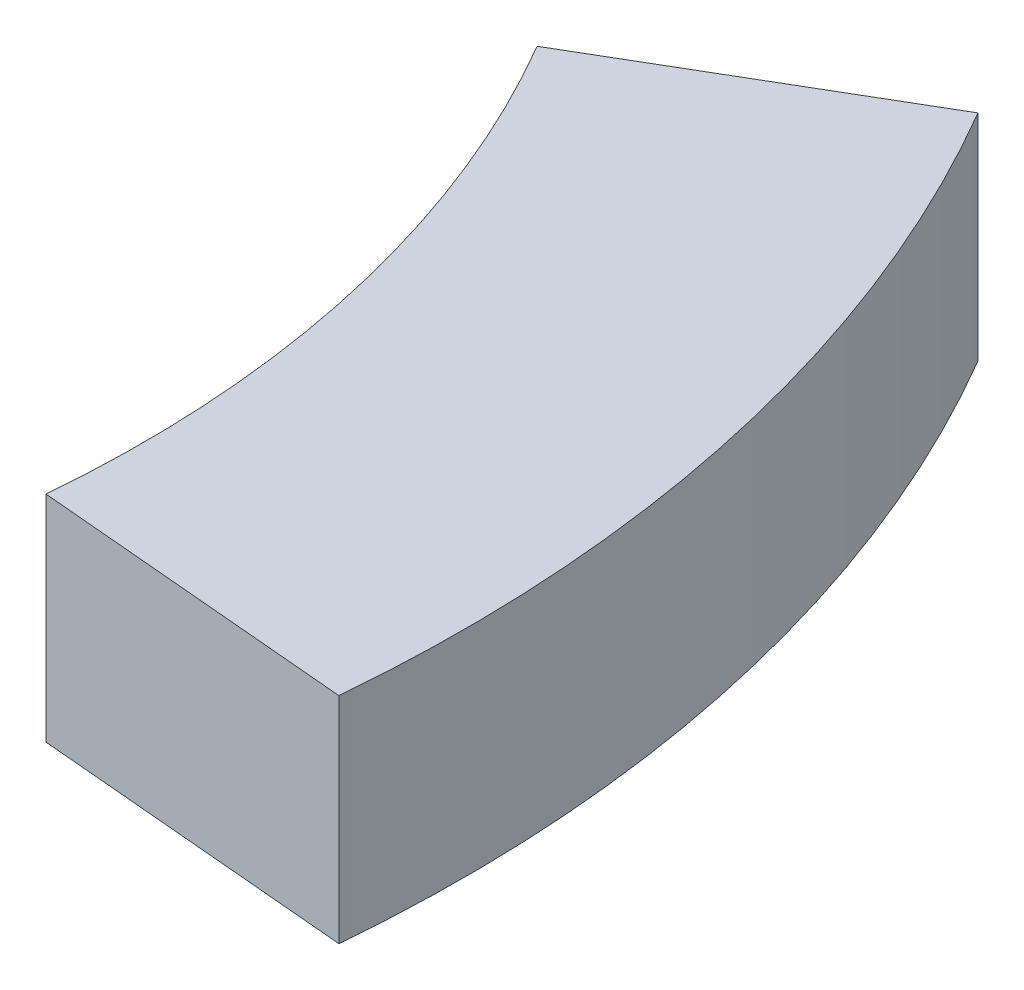
SolidWorks part; units mm, degrees
ref_plane "Front Plane" through (0, 0, 0) normal (0, 0, 1) x (1, 0, 0)
ref_plane "Top Plane" through (0, 0, 0) normal (0, 1, 0) x (1, 0, 0)
ref_plane "Right Plane" through (0, 0, 0) normal (1, 0, 0) x (0, 0, -1)
sketch "Sketch1" plane through (0, 0, 0) normal (0, 1, 0) x (1, 0, 0)
  line L0 (0, 0) -> (57.28, 0) construction
  line L1 (42.9687, 25.1345) -> (55.9162, 32.7082)
  line L2 (49.59, -4.3453) -> (64.5327, -5.6547)
  circle A0 centre (0, 0) radius 57.28 construction
  arc A1 (57.0614, -5) -> (49.4424, 28.9213) centre (0, 0) ccw construction
  arc A2 (64.5327, -5.6547) -> (55.9162, 32.7082) centre (0, 0) ccw
  arc A3 (49.59, -4.3453) -> (42.9687, 25.1345) centre (0, 0) ccw
  arc A4 (49.59, -4.3453) -> (64.5327, -5.6547) centre (57.0614, -5) ccw
  arc A5 (55.9162, 32.7082) -> (42.9687, 25.1345) centre (49.4424, 28.9213) ccw
  point P3 (51.7762, 24.4994)
  point P5 (55.8876, 12.5527)
  point P7 (57.28, 0)
  dimension "D1" = 114.56
  dimension "D5" = 7.5
  dimension "D2" = 25.11
  dimension "D3" = 5
  dimension "D4" = 5
extrude "Boss-Extrude1" add sketch "Sketch1" along normal blind 10 contours A3 L2 A2 L1
sketch "Sketch2" plane through (0, 0, 0) normal (0, -1, 0) x (-1, 0, 0)
  point P0 (-57.28, 0)
  point P3 (-51.7762, 24.4994)
hole_wizard "Ø5.0mm Dowel Hole1" positions "Sketch2" profile "Sketch3" hole size "Ø5.0" standard "ANSI Metric"
sketch "Sketch3" plane through (57.28, 0, 0) normal (1, 0, 0) x (0, 0, -1)
  line L0 (0, 0) -> (0, 7.5022)
  line L1 (0, 7.5022) -> (2.5, 6)
  line L2 (2.5, 6) -> (2.5, 0)
  line L5 (2.5, 0) -> (0, 0)
  line L10 (0, 7.5022) -> (-2.5, 6) construction
  line L11 (0, -6.35) -> (0, 107.95) construction
  dimension "Hole Dia." = 5
  dimension "Hole Depth" = 6
  dimension "Drill Angle" = 118
